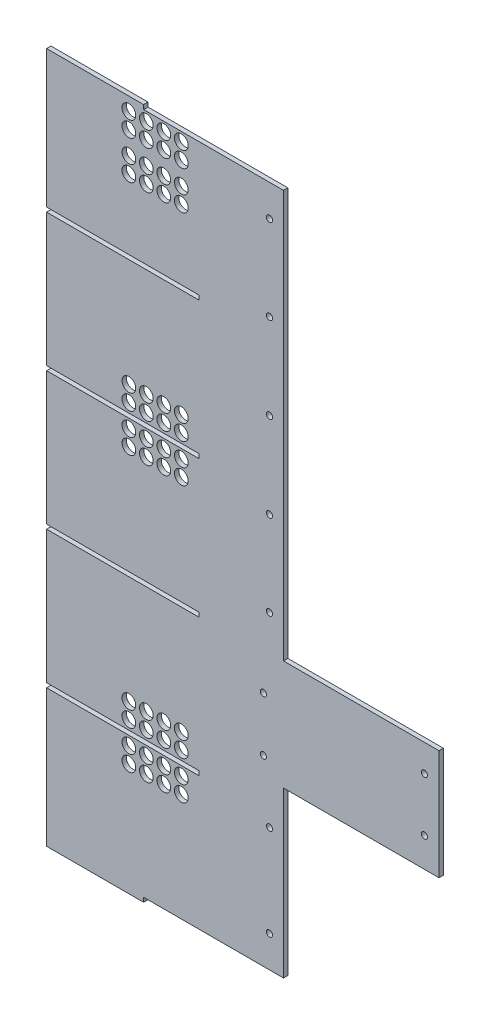
SolidWorks part; units mm, degrees
material "6061-T6 (SS)"
ref_plane "X-Y Datum" through (0, 0, 0) normal (0, 0, 1) x (1, 0, 0)
ref_plane "X-Z Datum" through (0, 0, 0) normal (0, 1, 0) x (1, 0, 0)
ref_plane "Y-Z Datum" through (0, 0, 0) normal (1, 0, 0) x (0, 0, -1)
sketch "Sketch1" plane through (0, 0, 0) normal (0, 0, 1) x (1, 0, 0)
  line L1 (129.0131, 254.2454) -> (-18.6854, 254.2454)
  line L3 (129.0131, -241.3467) -> (-18.6854, -241.3467)
  line L4 (-18.6854, 254.2454) -> (-18.6854, 157.667)
  line L24 (129.0131, 254.2454) -> (129.0131, -241.3467)
  line L25 (92.0885, 157.667) -> (-18.6854, 157.667)
  line L27 (92.0885, 154.492) -> (-18.6854, 154.492)
  line L29 (92.0885, 57.9136) -> (-18.6854, 57.9136)
  line L31 (92.0885, 54.7386) -> (-18.6854, 54.7386)
  line L33 (92.0885, -41.8399) -> (-18.6854, -41.8399)
  line L35 (92.0885, -45.0149) -> (-18.6854, -45.0149)
  line L37 (92.0885, -141.5933) -> (-18.6854, -141.5933)
  line L39 (92.0885, -144.7683) -> (-18.6854, -144.7683)
  line L41 (92.0885, -141.5933) -> (92.0885, -144.7683)
  line L42 (92.0885, -41.8399) -> (92.0885, -45.0149)
  line L43 (92.0885, 57.9136) -> (92.0885, 54.7386)
  line L44 (-18.6854, -144.7683) -> (-18.6854, -241.3467)
  line L45 (-18.6854, -45.0149) -> (-18.6854, -141.5933)
  line L46 (-18.6854, 54.7386) -> (-18.6854, -41.8399)
  line L47 (-18.6854, 154.492) -> (-18.6854, 57.9136)
  line L48 (92.0885, 157.667) -> (92.0885, 154.492)
extrude "Boss-Extrude2" add sketch "Sketch1" along normal blind 3.175
sketch "Sketch2" plane through (0, 0, 3.175) normal (0, 0, 1) x (1, 0, 0)
  line L0 (129.0131, -241.3467) -> (153.4072, -227.2627) construction
  line L2 (129.0131, 254.2454) -> (129.0131, -241.3467)
  line L15 (153.4072, -227.2627) -> (153.4072, -187.8927)
  line L18 (153.4072, -143.1808) -> (153.4072, 240.1614)
  line L19 (153.4072, 240.1614) -> (153.4072, 254.2454)
  line L21 (153.4072, -187.8927) -> (153.4072, -143.1808)
  line L22 (153.4072, 254.2454) -> (129.0131, 254.2454)
  line L23 (129.0131, -241.3467) -> (153.4072, -241.3467)
  line L24 (153.4072, -241.3467) -> (153.4072, -227.2627)
extrude "Boss-Extrude3" add sketch "Sketch2" against normal through all
sketch "Sketch3" plane through (0, 0, 3.175) normal (0, 0, 1) x (1, 0, 0)
  line L8 (153.4072, 6.4494) -> (-81.8872, 6.4494) construction
  line L9 (51.8072, 257.4204) -> (51.8072, 254.2454)
  line L18 (153.4072, 257.4204) -> (51.8072, 257.4204)
  line L19 (153.4072, 257.4204) -> (153.4072, 270.1204)
  line L20 (153.4072, 270.1204) -> (30.4963, 270.1204)
  line L21 (30.4963, 270.1204) -> (6.7146, 286.3764)
  line L22 (-18.6854, 286.3764) -> (6.7146, 286.3764)
  line L23 (-18.6854, 254.2454) -> (-18.6854, 286.3764)
  line L24 (51.8072, 254.2454) -> (-18.6854, 254.2454)
extrude "Boss-Extrude4" [suppressed] add sketch "Sketch3" against normal through all
sketch "Sketch4" [suppressed] plane through (0, 0, 3.175) normal (0, 0, 1) x (1, 0, 0)
  line L1 (153.4072, 270.1204) -> (221.7231, 270.1204)
  line L2 (153.4072, 270.1204) -> (153.4072, 257.4204)
  line L3 (153.4072, 257.4204) -> (221.7231, 257.4204)
  line L4 (221.7231, 270.1204) -> (221.7231, 257.4204)
  line L5 (153.4072, 254.2454) -> (221.7231, 254.2454)
  line L6 (153.4072, 254.2454) -> (153.4072, 157.667)
  line L7 (153.4072, 157.667) -> (221.7231, 157.667)
  line L8 (221.7231, 254.2454) -> (221.7231, 157.667)
  dimension "D1" = 68.3158
extrude "Boss-Extrude5" [suppressed] add sketch "Sketch4" against normal through all
sketch "Sketch7" plane through (0, 0, 3.175) normal (0, 0, 1) x (1, 0, 0)
  line L0 (92.0885, -41.8399) -> (153.4072, -41.8399) construction
  line L1 (153.2294, -121.7811) -> (153.4072, -41.8399)
  line L2 (153.4072, -241.3467) -> (153.4072, 254.2454) construction
  line L3 (153.4072, -41.8399) -> (266.4372, -41.8399)
  line L4 (266.4372, -41.8399) -> (266.4372, -121.7811)
  line L5 (266.4372, -121.7811) -> (153.2294, -121.7811)
  line L6 (153.4072, -241.3467) -> (153.4072, 254.2454) construction
extrude "Boss-Extrude6" add sketch "Sketch7" against normal through all
sketch "Sketch8" plane through (0, 0, 3.175) normal (0, 0, 1) x (1, 0, 0)
  line L1 (-18.6854, 254.2454) -> (51.8072, 254.2454)
  line L2 (-18.6854, 254.2454) -> (-18.6854, 257.4204)
  line L3 (-18.6854, 257.4204) -> (51.8072, 257.4204)
  line L4 (51.8072, 254.2454) -> (51.8072, 257.4204)
  line L5 (-18.6854, -241.3467) -> (51.8072, -241.3467)
  line L6 (-18.6854, -241.3467) -> (-18.6854, -244.5217)
  line L7 (-18.6854, -244.5217) -> (51.8072, -244.5217)
  line L8 (51.8072, -241.3467) -> (51.8072, -244.5217)
extrude "Boss-Extrude7" add sketch "Sketch8" against normal through all
sketch "Sketch12" plane through (0, 0, 3.175) normal (0, 0, 1) x (1, 0, 0)
  line L0 (-18.6854, 257.4204) -> (289.5814, 257.4204) construction
  line L1 (-18.6854, 257.4204) -> (-18.6854, -144.2662) construction
  line L2 (-18.6854, -144.2662) -> (289.5814, -144.2662) construction
  line L3 (289.5814, 257.4204) -> (289.5814, -144.2662) construction
  point P0 (143.2472, 244.0133)
  point P1 (143.2472, 171.1213)
  point P2 (143.2472, 98.2292)
  point P3 (143.2472, 25.3372)
  point P4 (143.2472, -47.5549)
  point P5 (170.6792, -74.9869)
  point P6 (210.7117, -74.9869)
  point P7 (250.7441, -74.9869)
  point P8 (256.2772, -80.52)
  point P9 (256.2772, -106.7475)
  point P10 (256.2772, -132.9751)
  point P15 (143.2472, -160.6738)
  point P16 (143.2472, -195.8942)
  point P17 (143.2472, -231.1146)
sketch "Sketch14" plane through (0, 0, 0) normal (0, 0, -1) x (-1, 0, 0)
  line L0 (18.6854, -244.5217) -> (-23.3644, -244.5217) construction
  line L1 (18.6854, -244.5217) -> (18.6854, -226.8054) construction
  line L2 (18.6854, -226.8054) -> (-23.3644, -226.8054) construction
  line L3 (-23.3644, -244.5217) -> (-23.3644, -226.8054) construction
  line L4 (-258.5632, -117.2684) -> (-255.7997, -117.2684) construction
  line L5 (-255.7997, -117.2684) -> (-255.7997, -100.4453) construction
  circle A0 centre (-143.2472, -218.4146) radius 2.25
  circle A1 centre (-143.2472, -151.7533) radius 2.25
  circle A2 centre (-255.7997, -100.4453) radius 2.25
  circle A3 centre (-255.7997, -61.597) radius 2.25
  circle A4 centre (-143.2472, -16.4399) radius 2.25
  circle A5 centre (-143.2472, 45.2329) radius 2.25
  circle A6 centre (-143.2472, 107.4367) radius 2.25
  circle A7 centre (-143.2472, 169.6405) radius 2.25
  circle A8 centre (-143.2472, 231.3133) radius 2.25
  point P0 (-143.2472, -218.4146)
  point P1 (-143.2472, -151.7533)
  point P2 (-255.7997, -100.4453)
  point P3 (-255.7997, -61.597)
  point P4 (-143.2472, -16.4399)
  point P5 (-143.2472, 45.2329)
  point P6 (-143.2472, 107.4367)
  point P7 (-143.2472, 169.6405)
  point P8 (-143.2472, 231.3133)
  point P13 (18.6854, -244.5217)
  point P34 (-255.7997, -61.597)
  point P36 (18.6854, -244.5217)
extrude "Cut-Extrude1" cut sketch "Sketch14" against normal through all
sketch "Sketch15" plane through (0, 0, 0) normal (0, 0, -1) x (-1, 0, 0)
  line L0 (-141.8421, -108.5523) -> (-135.7421, -108.5523) construction
  line L1 (-141.8421, -69.242) -> (-135.7421, -69.242) construction
  line L2 (-266.4372, -121.7811) -> (-206.1233, -121.7811) construction
  line L3 (-266.4372, -121.7811) -> (-266.4372, -88.3371) construction
  line L4 (-266.4372, -88.3371) -> (-206.1233, -88.3371) construction
  line L5 (-206.1233, -121.7811) -> (-206.1233, -88.3371) construction
  circle A0 centre (-138.7921, -108.5523) radius 2.25
  circle A1 centre (-138.7921, -69.242) radius 2.25
  point P12 (-266.4372, -121.7811)
extrude "Cut-Extrude2" cut sketch "Sketch15" against normal through all
sketch "Sketch16" plane through (0, 0, 3.175) normal (0, 0, 1) x (1, 0, 0)
  line L0 (92.0885, 156.0795) -> (84.4685, 156.0795) construction
  line L1 (92.0885, 157.667) -> (92.0885, 154.492) construction
  line L2 (92.0885, -143.1808) -> (84.4685, -143.1808) construction
  line L3 (92.0885, -141.5933) -> (92.0885, -144.7683) construction
  line L4 (92.0885, 56.3261) -> (84.4685, 56.3261) construction
  line L5 (84.4685, -118.1808) -> (34.4685, -118.1808) construction
  line L6 (84.4685, -118.1808) -> (84.4685, -168.1808) construction
  line L7 (84.4685, -168.1808) -> (34.4685, -168.1808) construction
  line L8 (34.4685, -118.1808) -> (34.4685, -168.1808) construction
  line L9 (92.0885, 57.9136) -> (92.0885, 54.7386) construction
  line L10 (92.0885, -143.1808) -> (84.4685, -143.1808) construction
  line L11 (34.4685, 81.3261) -> (84.4685, 81.3261) construction
  line L12 (34.4685, 81.3261) -> (34.4685, 31.3261) construction
  line L13 (34.4685, 31.3261) -> (84.4685, 31.3261) construction
  line L14 (84.4685, 81.3261) -> (84.4685, 31.3261) construction
  line L15 (34.4685, -118.1808) -> (84.4685, -118.1808) construction
  line L16 (34.4685, -118.1808) -> (34.4685, -168.1808) construction
  line L17 (34.4685, -168.1808) -> (84.4685, -168.1808) construction
  line L18 (84.4685, -118.1808) -> (84.4685, -168.1808) construction
  line L19 (92.0885, 228.038) -> (84.4685, 228.038) construction
  line L20 (34.4685, 253.038) -> (84.4685, 253.038) construction
  line L21 (34.4685, 253.038) -> (34.4685, 203.038) construction
  line L22 (34.4685, 203.038) -> (84.4685, 203.038) construction
  line L23 (84.4685, 253.038) -> (84.4685, 203.038) construction
  circle A1 centre (79.1915, 75.9754) radius 5
  circle A2 centre (66.4915, 75.9754) radius 5
  circle A3 centre (53.7915, 75.9754) radius 5
  circle A4 centre (41.0915, 75.9754) radius 5
  circle A5 centre (66.4915, 64.5454) radius 5
  circle A6 centre (53.7915, 64.5454) radius 5
  circle A7 centre (41.0915, 64.5454) radius 5
  circle A8 centre (79.1915, 64.5454) radius 5
  circle A9 centre (41.0915, 36.6767) radius 5
  circle A10 centre (41.0915, 48.1067) radius 5
  circle A11 centre (53.7915, 36.6767) radius 5
  circle A12 centre (53.7915, 48.1067) radius 5
  circle A13 centre (66.4915, 36.6767) radius 5
  circle A14 centre (66.4915, 48.1067) radius 5
  circle A15 centre (79.1915, 48.1067) radius 5
  circle A16 centre (79.1915, 36.6767) radius 5
  circle A17 centre (79.1915, -123.5314) radius 5
  circle A18 centre (66.4915, -123.5314) radius 5
  circle A19 centre (53.7915, -123.5314) radius 5
  circle A20 centre (41.0915, -123.5314) radius 5
  circle A21 centre (66.4915, -134.9614) radius 5
  circle A22 centre (53.7915, -134.9614) radius 5
  circle A23 centre (41.0915, -134.9614) radius 5
  circle A24 centre (79.1915, -134.9614) radius 5
  circle A25 centre (41.0915, -162.8301) radius 5
  circle A26 centre (41.0915, -151.4001) radius 5
  circle A27 centre (53.7915, -162.8301) radius 5
  circle A28 centre (53.7915, -151.4001) radius 5
  circle A29 centre (66.4915, -162.8301) radius 5
  circle A30 centre (66.4915, -151.4001) radius 5
  circle A31 centre (79.1915, -151.4001) radius 5
  circle A32 centre (79.1915, -162.8301) radius 5
  circle A33 centre (79.1915, 247.6873) radius 5
  circle A34 centre (66.4915, 247.6873) radius 5
  circle A35 centre (53.7915, 247.6873) radius 5
  circle A36 centre (41.0915, 247.6873) radius 5
  circle A37 centre (66.4915, 236.2573) radius 5
  circle A38 centre (53.7915, 236.2573) radius 5
  circle A39 centre (41.0915, 236.2573) radius 5
  circle A40 centre (79.1915, 236.2573) radius 5
  circle A41 centre (41.0915, 208.3886) radius 5
  circle A42 centre (41.0915, 219.8186) radius 5
  circle A43 centre (53.7915, 208.3886) radius 5
  circle A44 centre (53.7915, 219.8186) radius 5
  circle A45 centre (66.4915, 208.3886) radius 5
  circle A46 centre (66.4915, 219.8186) radius 5
  circle A47 centre (79.1915, 219.8186) radius 5
  circle A48 centre (79.1915, 208.3886) radius 5
  dimension "D1" = 4
  dimension "D2" = 2
extrude "Cut-Extrude3" cut sketch "Sketch16" against normal through all
